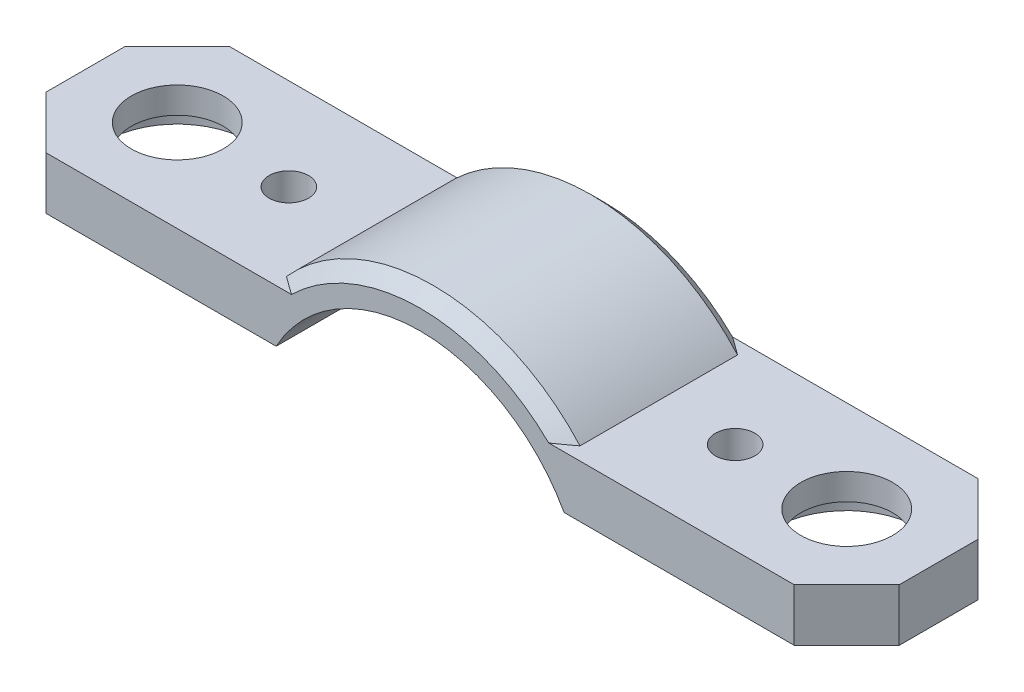
SolidWorks part; units mm, degrees
ref_plane "Plan de face" through (0, 0, 0) normal (0, 0, 1) x (1, 0, 0)
ref_plane "Plan de dessus" through (0, 0, 0) normal (0, 1, 0) x (1, 0, 0)
ref_plane "Plan de droite" through (0, 0, 0) normal (1, 0, 0) x (0, 0, -1)
sketch "Esquisse2" plane through (0, 0, 0) normal (0, 1, 0) x (1, 0, 0)
  line L1 (-35.8261, 4.6472) -> (29.1739, 4.6472)
  line L2 (-35.8261, 4.6472) -> (-35.8261, -9.3528)
  line L3 (-35.8261, -9.3528) -> (29.1739, -9.3528)
  line L4 (29.1739, 4.6472) -> (29.1739, -9.3528)
  dimension "D1" = 65
  dimension "D6" = 14
extrude "Boss.-Extru.1" add sketch "Esquisse2" against normal blind 4
sketch "Esquisse3" plane through (0, -4, 0) normal (0, -1, 0) x (1, 0, 0)
  line L0 (-35.8261, 2.3528) -> (29.1739, 2.3528) construction
  line L1 (-35.8261, -4.6472) -> (-35.8261, 9.3528) construction
  line L2 (29.1739, 9.3528) -> (29.1739, -4.6472) construction
  circle A0 centre (-28.8261, 2.3528) radius 5.5
  circle A1 centre (22.1739, 2.3528) radius 5.5
  dimension "D1" = 11
  dimension "D2" = 11
  dimension "D3" = 7
  dimension "D4" = 7
extrude "Enlèv. mat.-Extru.1" cut sketch "Esquisse3" against normal blind 2
sketch "Esquisse4" plane through (0, -2, 0) normal (0, -1, 0) x (1, 0, 0)
  circle A0 centre (-28.8261, 2.3528) radius 3.5
  circle A1 centre (22.1739, 2.3528) radius 3.5
  dimension "D1" = 7
  dimension "D2" = 7
extrude "Enlèv. mat.-Extru.2" cut sketch "Esquisse4" against normal through all
sketch "Esquisse5" plane through (0, 0, -4.6472) normal (0, 0, -1) x (-1, 0, 0)
  line L0 (-29.1739, 0) -> (-29.1739, -26.7463) construction
  line L1 (35.8261, 0) -> (35.8261, -25.6795) construction
  line L2 (-29.1739, -10) -> (35.8261, -10) construction
  line L3 (-29.1739, 0) -> (35.8261, 0) construction
  line L4 (-10.4216, -4) -> (17.0738, -4)
  line L5 (-29.1739, -4) -> (35.8261, -4) construction
  arc A0 (17.0738, -4) -> (-10.4216, -4) centre (3.3261, -10) ccw
  dimension "D2" = 30
  dimension "D1" = 10
extrude "Boss.-Extru.3" add sketch "Esquisse5" against normal blind 14
sketch "Esquisse7" plane through (0, 0, -4.6472) normal (0, 0, -1) x (-1, 0, 0)
  circle A0 centre (3.3261, -10) radius 12.5
  dimension "D1" = 25
extrude "Enlèv. mat.-Extru.4" cut sketch "Esquisse7" against normal through all
sketch "Esquisse8" plane through (0, 0, 0) normal (0, 1, 0) x (1, 0, 0)
  line L0 (-35.8261, -2.3528) -> (29.1739, -2.3528) construction
  line L1 (-35.8261, 4.6472) -> (-35.8261, -9.3528) construction
  line L2 (29.1739, -9.3528) -> (29.1739, 4.6472) construction
  circle A0 centre (-20.3261, -2.3528) radius 1.5
  circle A1 centre (13.6739, -2.3528) radius 1.5
  circle A2 centre (-28.8261, -2.3528) radius 3.5 construction
  circle A3 centre (22.1739, -2.3528) radius 3.5 construction
  dimension "D1" = 8.5
  dimension "D2" = 8.5
extrude "Enlèv. mat.-Extru.5" cut sketch "Esquisse8" against normal through all
chamfer "Chanfrein1" distance 1 angle 45 2 edges at (-3.3261, 5, 9.3528) (-3.3261, 5, -4.6472)
chamfer "Chanfrein2" distance 4 angle 45 4 edges at (29.1739, -2, 9.3528) (29.1739, -2, -4.6472) (-35.8261, -2, 9.3528) (-35.8261, -2, -4.6472)
